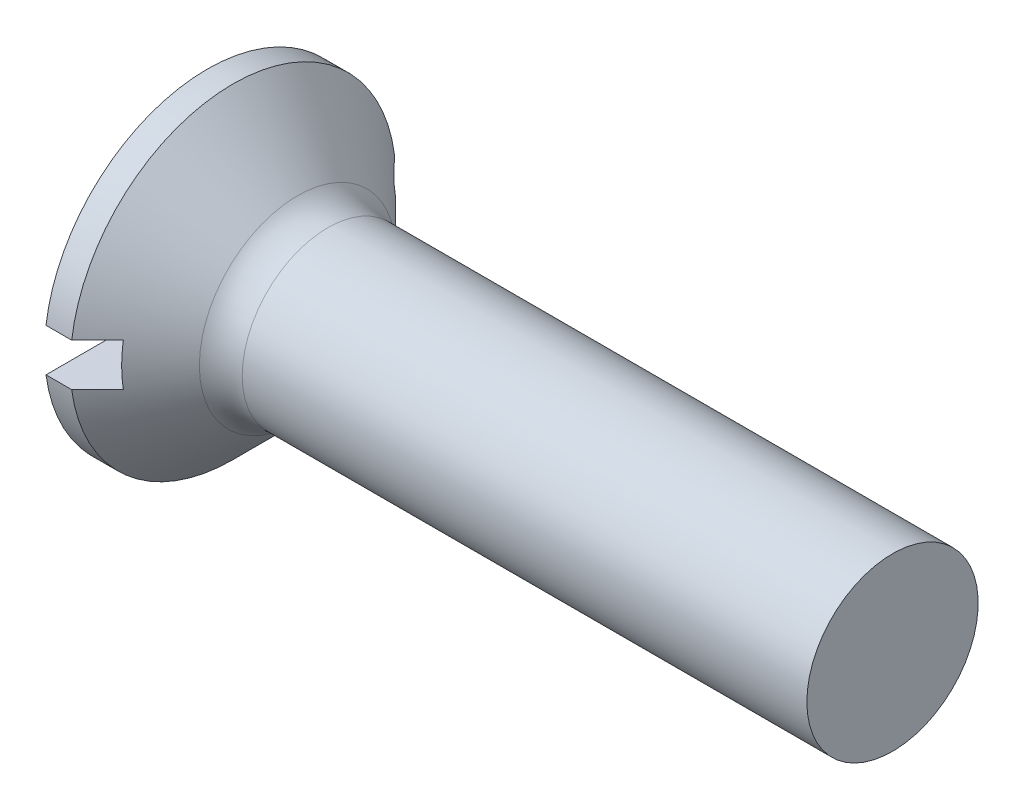
SolidWorks part; units mm, degrees
revolve "Base-Revolve" add sketch "BodySke" angle 360 about L5
sketch "BodySke" plane through (0, 0, 0) normal (0, 0, 1) x (1, 0, 0)
  line L0 (0, 0) -> (0, 1.9)
  line L1 (0, 1.9) -> (0.3, 1.9)
  line L2 (1.2, 1) -> (8, 1)
  line L3 (8, 1) -> (8, 0)
  line L4 (8, 0) -> (0, 0)
  line L5 (-6.35, 0) -> (82.55, 0) construction
  line L6 (1.2, -1) -> (8, -1) construction
  line L7 (0.3, -1.9) -> (1.2, -1) construction
  line L8 (0.3, 1.9) -> (1.2, 1)
  line L9 (0, -1.9) -> (0.3, -1.9) construction
  line L10 (1.6, 2.5875) -> (1.6, -6.9375) construction
  line L11 (0, 6.35) -> (0, -3.175) construction
  dimension "Diameter" = 2
  dimension "Length" = 8
  dimension "Head_ht" = 1.2
  dimension "Head_dia" = 3.8
  dimension "Head_ang" = 90
  dimension "D6" = 0.3
  dimension "Advance" = 0.4
  dimension "Thread_nom" = 8
cosmetic thread "ThreadCosmetic" [suppressed] parameters "Thread_length"=6.4, "Thread_minor"=1.548
extrude "Slot" cut sketch "Sketch2" against normal blind 0.6
sketch "Sketch2" plane through (0, 0, 0) normal (-1, 0, 0) x (0, 0, 1)
  line L0 (-1.9, -0.25) -> (1.9, -0.25)
  line L1 (-1.9, -0.25) -> (-1.9, 0.25)
  line L2 (1.9, 0.25) -> (-1.9, 0.25)
  line L3 (1.9, 0.25) -> (1.9, -0.25)
  dimension "Slot_width" = 0.5
  dimension "D1" = 0.25
  dimension "D2" = 3.8
  dimension "D3" = 1.9
ref_plane "Plane1" through (0, 0, 0) normal (0, 0, 1) x (1, 0, 0)
ref_plane "Plane2" through (0, 0, 0) normal (0, 1, 0) x (1, 0, 0)
ref_plane "Plane3" through (0, 0, 0) normal (1, 0, 0) x (0, 0, -1)
fillet "Fillet1" radius 0.5 1 edges at (1.2, 0, 1)
sketch "ThdSchSke" plane through (0, 0, 0) normal (0, 0, 1) x (1, 0, 0)
  line L0 (1.6, -0.774) -> (1.4418, -1)
  line L1 (1.6, -0.774) -> (1.7582, -1)
  line L2 (1.7582, -1) -> (1.7582, -1.25)
  line L3 (-3.175, 0) -> (5.1513, 0) construction
  line L5 (1.7582, -1.25) -> (1.4418, -1.25)
  line L6 (1.4418, -1.25) -> (1.4418, -1)
  line L7 (0, 1.9) -> (0, 0.25) construction
  dimension "Diameter" = 2
  dimension "Thread_minor" = 1.548
  dimension "Start" = 1.6
revolve "ThreadSchematic" [suppressed] cut sketch "ThdSchSke" angle 360 about L3
pattern_linear "ThdSchPat" [suppressed]
equation "\"D1@Sketch2\" = \"Slot_width@Sketch2\" / 2"
equation "\"D2@Sketch2\" = \"Head_dia@BodySke\""
equation "\"D3@Sketch2\" = \"D2@Sketch2\" / 2"
equation "\"Thread_length@ThreadCosmetic\" = ((sgn( (\"Length@BodySke\" - \"Advance@BodySke\" * 1.0 - \"Head_ht@BodySke\" ) - \"Thread_nom@BodySke\" )-1)*( (\"Length@BodySke\" - \"Advance@BodySke\" * 1.0 - \"Head_ht@BodySke\" ) - \"Thread_nom@BodySke\" ))/-2+ \"Thread_nom@BodySke\""
equation "\"Thread_minor@ThdSchSke\" = \"Thread_minor@ThreadCosmetic\""
equation "\"Diameter@ThdSchSke\" = \"Diameter@BodySke\""
equation "\"Overcut@ThdSchSke\" = \"Diameter@BodySke\" * 1.25"
equation "\"Start@ThdSchSke\" = 0.000001 + \"Length@BodySke\" - \"Thread_length@ThreadCosmetic\"  '---Countersunk---"
equation "\"Num_threads@ThdSchPat\" = int( \"Thread_length@ThreadCosmetic\" / \"Advance@BodySke\" + 0.999 )  + 1"
equation "\"Advance@ThdSchPat\" = \"Thread_length@ThreadCosmetic\" /  (\"Num_threads@ThdSchPat\" - 1) 'relax it"
